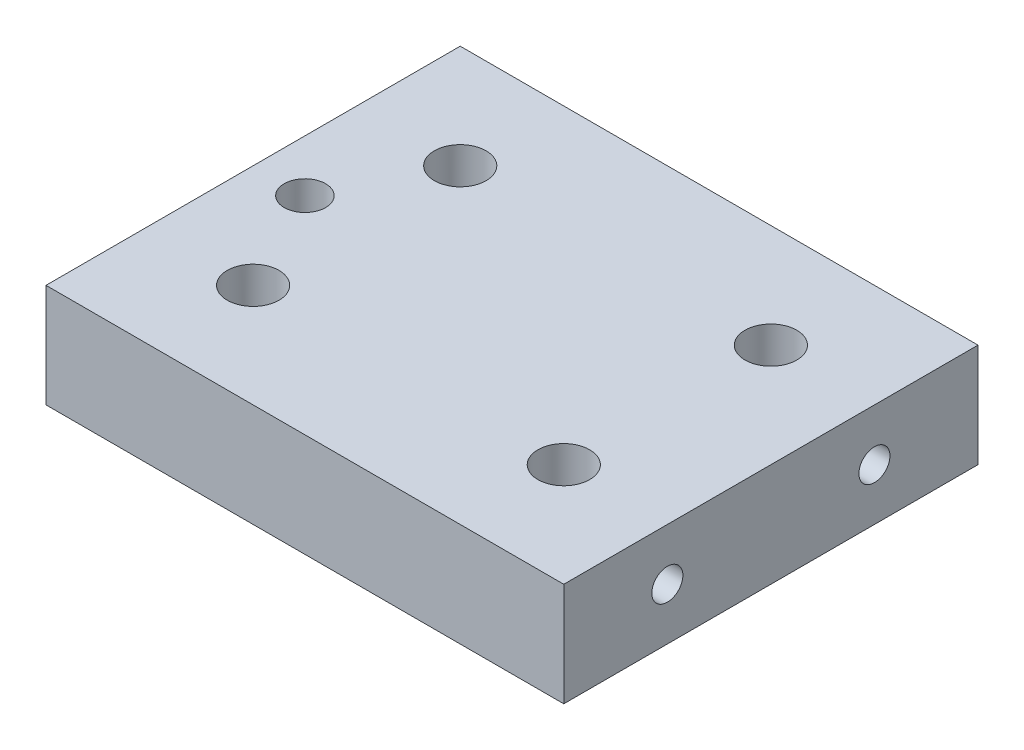
SolidWorks part; units mm, degrees
material "Сосна"
ref_plane "Спереди" through (0, 0, 0) normal (0, 0, 1) x (1, 0, 0)
ref_plane "Сверху" through (0, 0, 0) normal (0, 1, 0) x (1, 0, 0)
ref_plane "Справа" through (0, 0, 0) normal (1, 0, 0) x (0, 0, -1)
sketch "Эскиз1" plane through (0, 0, 0) normal (0, 1, 0) x (1, 0, 0)
  line L1 (0, 0) -> (100, 0)
  line L2 (0, 0) -> (0, 80)
  line L3 (0, 80) -> (100, 80)
  line L4 (100, 0) -> (100, 80)
  dimension "D1" = 100
  dimension "D2" = 80
extrude "Бобышка-Вытянуть1" add sketch "Эскиз1" along normal blind 20
sketch "Эскиз2" plane through (0, 0, 0) normal (0, -1, 0) x (1, 0, 0)
  line L0 (0, 0) -> (100, 0) construction
  line L1 (100, -80) -> (0, -80) construction
  line L2 (0, -80) -> (0, 0) construction
  line L3 (100, 0) -> (100, -80) construction
  line L4 (0, -40) -> (21.726, -40) construction
  circle A0 centre (20, -20) radius 5
  circle A1 centre (10, -40) radius 4
  circle A2 centre (20, -60) radius 5
  circle A3 centre (80, -20) radius 5
  circle A5 centre (80, -60) radius 5
  dimension "D1" = 20
  dimension "D7" = 10
  dimension "D9" = 10
  dimension "D10" = 20
  dimension "D16" = 10
  dimension "D18" = 10
  dimension "D3" = 8
  dimension "D2" = 20
  dimension "D4" = 20
  dimension "D5" = 10
  dimension "D6" = 20
  dimension "D11" = 20
  dimension "D13" = 20
  dimension "D15" = 20
extrude "Вырез-Вытянуть1" cut sketch "Эскиз2" against normal blind 20
sketch "Эскиз3" plane through (0, 0, 0) normal (-1, 0, 0) x (0, 0, 1)
  line L0 (-80, 10) -> (0, 10) construction
  line L1 (-80, 20) -> (-80, 0) construction
  line L2 (0, 20) -> (0, 0) construction
  circle A0 centre (-60, 10) radius 3
  circle A2 centre (-20, 10) radius 3
  dimension "D1" = 20
  dimension "D3" = 6
  dimension "D5" = 6
  dimension "D2" = 20
extrude "Вырез-Вытянуть2" cut sketch "Эскиз3" against normal blind 20
sketch "Эскиз4" plane through (100, 0, 0) normal (1, 0, 0) x (0, 0, -1)
  line L0 (0, 10) -> (80, 10) construction
  line L1 (0, 20) -> (0, 0) construction
  line L2 (80, 20) -> (80, 0) construction
  circle A0 centre (20, 10) radius 3
  circle A2 centre (60, 10) radius 3
  dimension "D1" = 20
  dimension "D3" = 6
  dimension "D5" = 6
  dimension "D2" = 20
extrude "Вырез-Вытянуть3" cut sketch "Эскиз4" against normal blind 20
